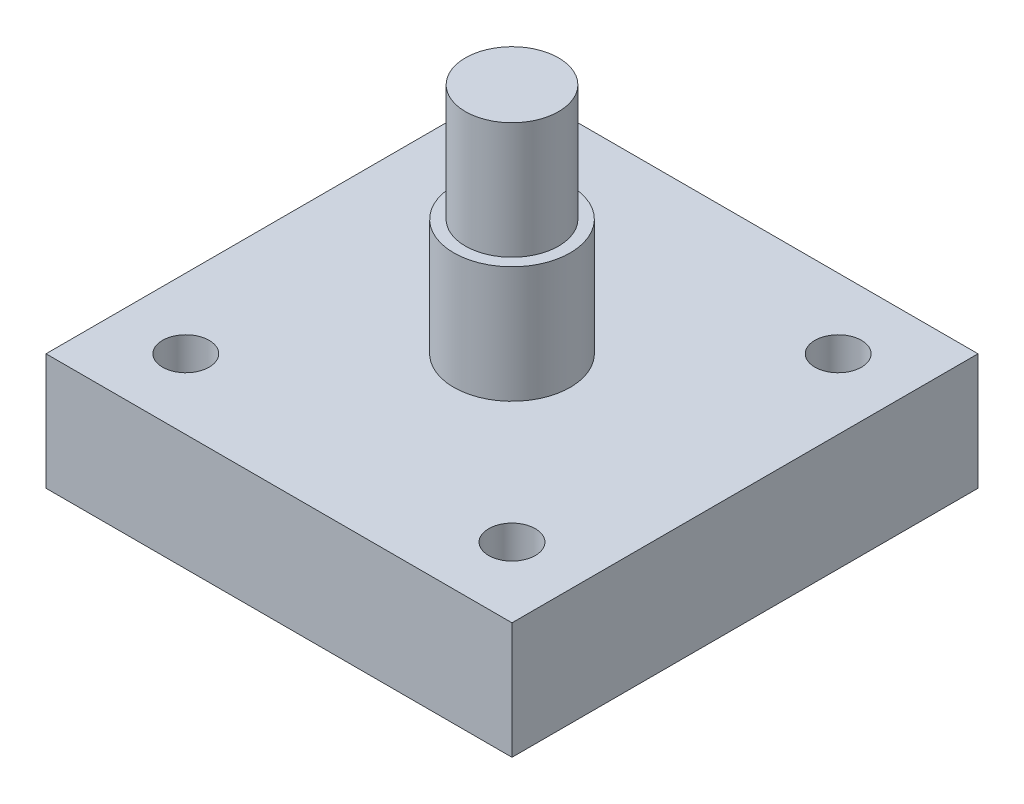
SolidWorks part; units mm, degrees
ref_plane "Front Plane" through (0, 0, 0) normal (0, 0, 1) x (1, 0, 0)
ref_plane "Top Plane" through (0, 0, 0) normal (0, 1, 0) x (1, 0, 0)
ref_plane "Right Plane" through (0, 0, 0) normal (1, 0, 0) x (0, 0, -1)
sketch "Sketch1" plane through (0, 0, 0) normal (0, 0, 1) x (1, 0, 0)
  line L1 (-10, 2.5) -> (10, 2.5)
  line L2 (-10, 2.5) -> (-10, -2.5)
  line L3 (-10, -2.5) -> (10, -2.5)
  line L4 (10, 2.5) -> (10, -2.5)
  line L5 (-10, 2.5) -> (10, -2.5) construction
  line L6 (-10, -2.5) -> (10, 2.5) construction
  point P0 (0, 0)
  dimension "D1" = 5
  dimension "D2" = 20
extrude "Boss-Extrude1" add sketch "Sketch1" along normal blind 20
sketch "Sketch2" plane through (0, 2.5, 0) normal (0, 1, 0) x (1, 0, 0)
  line L0 (10, -20) -> (-10, -20) construction
  line L1 (10, -20) -> (10, 0) construction
  circle A0 centre (0, -10) radius 2.5
  dimension "D1" = 5
  dimension "D2" = 10
  dimension "D3" = 10
extrude "Boss-Extrude2" add sketch "Sketch2" along normal blind 10
sketch "Sketch3" plane through (0, 2.5, 0) normal (0, 1, 0) x (1, 0, 0)
  line L0 (10, 0) -> (-10, 0) construction
  line L1 (10, -20) -> (-10, -20) construction
  line L2 (10, -20) -> (10, 0) construction
  circle A0 centre (-7, -3) radius 1
  circle A1 centre (7, -3) radius 1
  circle A2 centre (-7, -17) radius 1
  circle A3 centre (7, -17) radius 1
  dimension "D1" = 2
  dimension "D2" = 3
  dimension "D3" = 3
  dimension "D4" = 3
  dimension "D5" = 3
  dimension "D6" = 14
  dimension "D7" = 14
extrude "Cut-Extrude1" cut sketch "Sketch3" against normal through all
sketch "Sketch4" plane through (0, 12.5, 0) normal (0, 1, 0) x (1, 0, 0)
  circle A0 centre (0, -10) radius 2
  circle A3 centre (0, -10) radius 2.5 construction
  circle A4 centre (0, -10) radius 2.5 construction
  circle A5 centre (0, -10) radius 2.5
  dimension "D1" = 4
extrude "Cut-Extrude2" cut sketch "Sketch4" against normal blind 5
